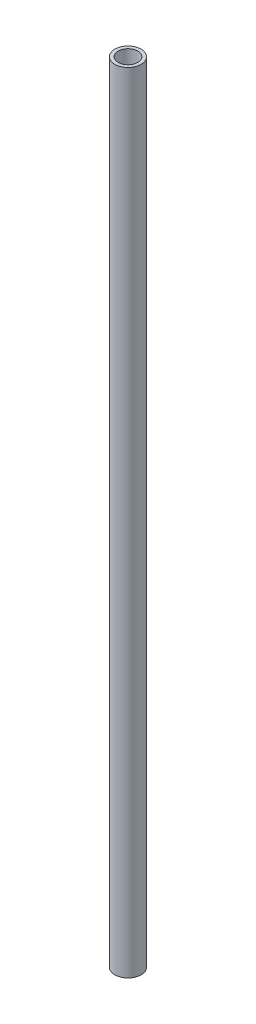
SolidWorks part; units mm, degrees
ref_plane "Front Plane" through (0, 0, 0) normal (0, 0, 1) x (1, 0, 0)
ref_plane "Top Plane" through (0, 0, 0) normal (0, 1, 0) x (1, 0, 0)
ref_plane "Right Plane" through (0, 0, 0) normal (1, 0, 0) x (0, 0, -1)
sketch "Sketch1" plane through (0, 0, 0) normal (0, 1, 0) x (1, 0, 0)
  circle A0 centre (0, 0) radius 1
  dimension "D1" = 2
extrude "Boss-Extrude1" add sketch "Sketch1" along normal blind 60
sketch "Sketch2" plane through (0, 0, 0) normal (0, -1, 0) x (1, 0, 0)
  circle A0 centre (0, 0) radius 0.75
extrude "Cut-Extrude1" cut sketch "Sketch2" against normal blind 60
